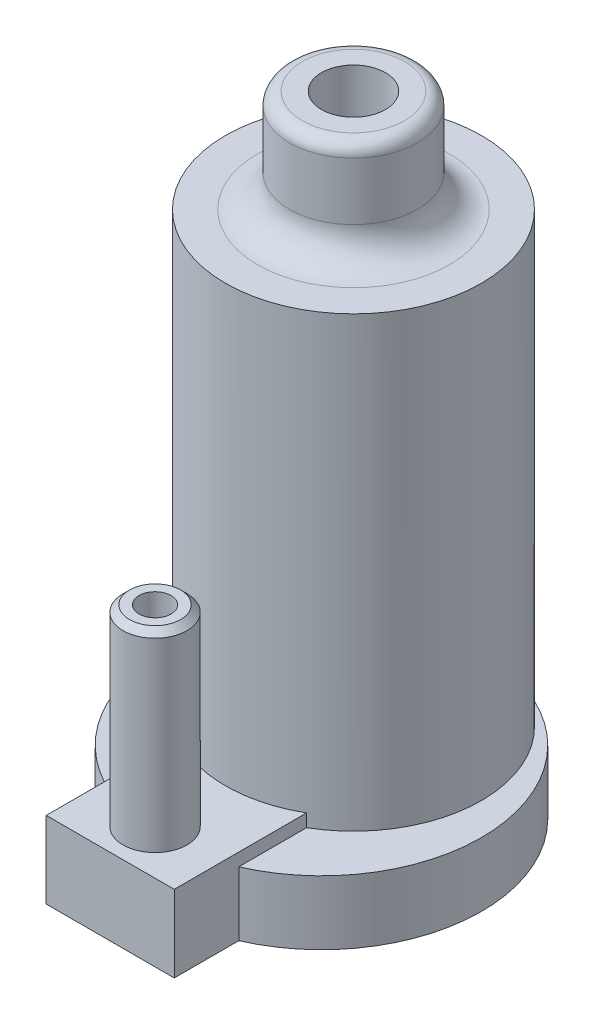
SolidWorks part; units mm, degrees
ref_plane "Спереди" through (0, 0, 0) normal (0, 0, 1) x (1, 0, 0)
ref_plane "Сверху" through (0, 0, 0) normal (0, 1, 0) x (1, 0, 0)
ref_plane "Справа" through (0, 0, 0) normal (1, 0, 0) x (0, 0, -1)
sketch "Эскиз1" plane through (0, 0, 0) normal (0, 1, 0) x (1, 0, 0)
  circle A0 centre (0, 0) radius 20
  dimension "D1" = 40
extrude "Бобышка-Вытянуть1" add sketch "Эскиз1" along normal blind 80
sketch "Эскиз2" plane through (0, 80, 0) normal (0, 1, 0) x (1, 0, 0)
  circle A0 centre (0, 0) radius 10
  dimension "D1" = 20
extrude "Бобышка-Вытянуть2" add sketch "Эскиз2" along normal blind 16
sketch "Эскиз3" plane through (0, 0, 0) normal (0, -1, 0) x (1, 0, 0)
  circle A0 centre (0, 5) radius 25
  circle A1 centre (0, 0) radius 20 construction
  point P2 (0, 10.558)
  point P4 (0, 0)
  point P5 (0, 3.5577)
  point P6 (0, 2.4062)
  dimension "D1" = 0
  dimension "D2" = 50
extrude "Бобышка-Вытянуть3" add sketch "Эскиз3" against normal blind 10
sketch "Эскиз4" plane through (0, 0, 0) normal (0, -1, 0) x (1, 0, 0)
  line L1 (-10, 38) -> (10, 38)
  line L2 (-10, 38) -> (-10, 0)
  line L3 (-10, 0) -> (10, 0)
  line L4 (10, 38) -> (10, 0)
  point P4 (0, 0)
  point P6 (11.0338, 37.805)
  dimension "D1" = 38
  dimension "D2" = 20
extrude "Бобышка-Вытянуть4" add sketch "Эскиз4" against normal blind 12
sketch "Эскиз5" plane through (0, 12, 0) normal (0, 1, 0) x (1, 0, 0)
  line L0 (10, -38) -> (-10, -38) construction
  circle A0 centre (0, -31) radius 5
  point P2 (0, 0)
  point P5 (0, -38)
  point P6 (0, 0)
  dimension "D1" = 10
  dimension "D2" = 2
extrude "Бобышка-Вытянуть5" add sketch "Эскиз5" along normal blind 30
fillet "Скругление1" radius 5 1 edges at (0, 80, 10)
fillet "Скругление2" radius 2 1 edges at (0, 96, 10)
sketch "Эскиз6" plane through (0, 96, 0) normal (0, 1, 0) x (1, 0, 0)
  circle A0 centre (0, 0) radius 5
  dimension "D1" = 10
extrude "Вырез-Вытянуть1" cut sketch "Эскиз6" against normal blind 30
sketch "Эскиз7" plane through (0, 42, 0) normal (0, 1, 0) x (1, 0, 0)
  circle A0 centre (0, -31) radius 2.5
  dimension "D1" = 5
extrude "Вырез-Вытянуть2" cut sketch "Эскиз7" against normal blind 30
chamfer "Фаска1" distance 1 angle 45 1 edges at (0, 42, 36)
